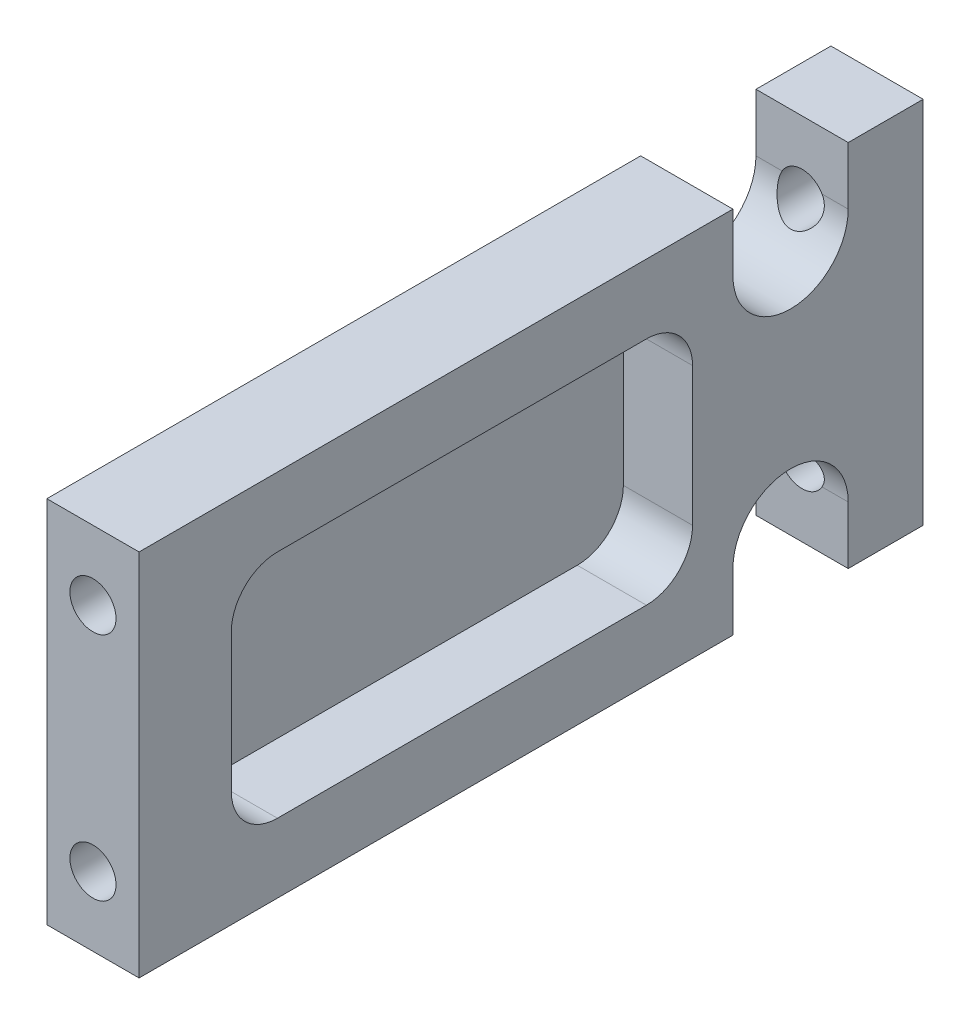
SolidWorks part; units mm, degrees
material "6061 Alloy"
ref_plane "Front Plane" through (0, 0, 0) normal (0, 0, 1) x (1, 0, 0)
ref_plane "Top Plane" through (0, 0, 0) normal (0, 1, 0) x (1, 0, 0)
ref_plane "Right Plane" through (0, 0, 0) normal (1, 0, 0) x (0, 0, -1)
sketch "Sketch1" plane through (0, 0, 0) normal (1, 0, 0) x (0, 0, -1)
  line L1 (0, 0) -> (107.95, 0)
  line L2 (0, 0) -> (0, 50.8)
  line L3 (0, 50.8) -> (107.95, 50.8)
  line L4 (107.95, 0) -> (107.95, 50.8)
  dimension "D1" = 107.95
  dimension "D2" = 50.8
extrude "Extrude1" add sketch "Sketch1" along normal blind 12.7
sketch "Sketch2" plane through (12.7, 0, 0) normal (1, 0, 0) x (0, 0, -1)
  line L0 (107.95, 50.8) -> (0, 50.8) construction
  line L1 (12.7, 41.275) -> (76.2, 41.275)
  line L2 (12.7, 41.275) -> (12.7, 9.525)
  line L3 (12.7, 9.525) -> (76.2, 9.525)
  line L4 (76.2, 41.275) -> (76.2, 9.525)
  line L5 (0, 50.8) -> (0, 0) construction
  dimension "D2" = 31.75
  dimension "D3" = 9.525
  dimension "D4" = 12.7
  dimension "D6" = 63.5
extrude "Cut-Extrude1" cut sketch "Sketch2" against normal blind 9.525
fillet "Fillet1" radius 6.35 4 edges at (7.9375, 9.525, -12.7) (7.9375, 41.275, -12.7) (7.9375, 41.275, -76.2) (7.9375, 9.525, -76.2)
sketch "Sketch3" plane through (12.7, 0, 0) normal (1, 0, 0) x (0, 0, -1)
  line L0 (97.6312, 50.8) -> (81.7562, 50.8)
  line L1 (107.95, 50.8) -> (0, 50.8) construction
  line L2 (81.7562, 50.8) -> (81.7562, 42.8625)
  line L3 (97.6312, 50.8) -> (97.6312, 42.8625)
  line L4 (107.95, 0) -> (107.95, 50.8) construction
  line L5 (97.6312, 0) -> (81.7562, 0)
  line L6 (0, 0) -> (107.95, 0) construction
  line L7 (81.7562, 0) -> (81.7562, 7.9375)
  line L8 (97.6312, 0) -> (97.6312, 7.9375)
  arc A0 (81.7562, 42.8625) -> (97.6312, 42.8625) centre (89.6937, 42.8625) ccw
  arc A1 (81.7562, 7.9375) -> (97.6312, 7.9375) centre (89.6937, 7.9375) cw
  dimension "D1" = 15.875
  dimension "D2" = 10.3187
  dimension "D3" = 7.9375
  dimension "D4" = 15.875
  dimension "D5" = 7.9375
  dimension "D6" = 10.3187
extrude "Cut-Extrude2" cut sketch "Sketch3" against normal through all
sketch "Sketch4" plane through (0, 0, 0) normal (0, 0, 1) x (1, 0, 0)
  line L0 (0, 50.8) -> (0, 0) construction
  line L1 (12.7, 50.8) -> (0, 50.8) construction
  line L2 (12.7, 0) -> (0, 0) construction
  circle A0 centre (6.35, 41.275) radius 3.175
  circle A1 centre (6.35, 9.525) radius 3.175
  point P8 (6.35, 0)
  dimension "D1" = 6.35
  dimension "D6" = 6.35
  dimension "D2" = 6.35
  dimension "D3" = 9.525
  dimension "D4" = 6.35
  dimension "D5" = 9.525
extrude "Cut-Extrude3" cut sketch "Sketch4" against normal blind 15.875
sketch "Sketch5" plane through (0, 0, -107.95) normal (0, 0, -1) x (-1, 0, 0)
  line L0 (-12.7, 0) -> (-12.7, 50.8) construction
  line L1 (-12.7, 50.8) -> (0, 50.8) construction
  line L3 (-12.7, 0) -> (0, 0) construction
  circle A0 centre (-6.35, 41.275) radius 3.175
  circle A1 centre (-6.35, 9.525) radius 3.175
  dimension "D1" = 6.35
  dimension "D2" = 6.35
  dimension "D3" = 6.35
  dimension "D4" = 6.35
  dimension "D5" = 9.525
  dimension "D6" = 9.525
extrude "Cut-Extrude4" cut sketch "Sketch5" against normal up to next
